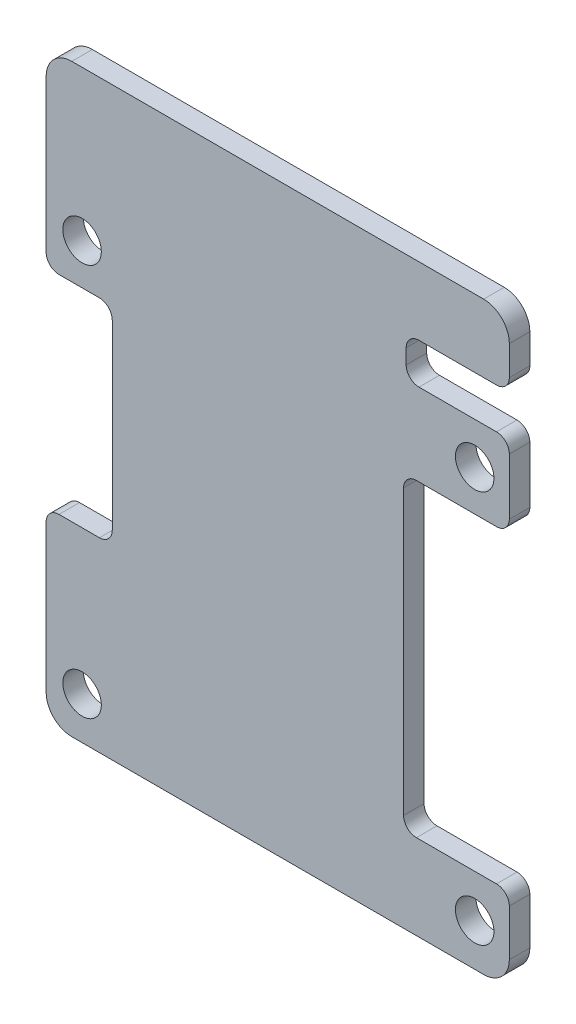
SolidWorks part; units mm, degrees
ref_plane "Front Plane" through (0, 0, 0) normal (0, 0, 1) x (1, 0, 0)
ref_plane "Top Plane" through (0, 0, 0) normal (0, 1, 0) x (1, 0, 0)
ref_plane "Right Plane" through (0, 0, 0) normal (1, 0, 0) x (0, 0, -1)
sketch "Board1"
  dimension "D3" = 2
  dimension "D1" = 54
  dimension "D2" = 36.1
  dimension "D6" = 30.6
  dimension "D7" = 30.6
  dimension "D8" = 30.6
  dimension "D10" = 2.7
  dimension "D9" = 3
  dimension "D4" = 11.7
  dimension "D5" = 30.6
sketch "Board2" plane through (0, 0, 0) normal (0, 0, 1) x (1, 0, 0)
  line L0 (115.6499, 52) -> (115.6499, 2)
  line L1 (117.6499, 0) -> (149.7499, 0)
  line L2 (151.7499, 2) -> (151.7499, 52)
  line L3 (149.7499, 54) -> (117.6499, 54)
  arc A0 (149.7499, 0) -> (151.7499, 2) centre (149.7499, 2) ccw
  arc A1 (115.6499, 2) -> (117.6499, 0) centre (117.6499, 2) ccw
  arc A2 (115.6499, 52) -> (117.6499, 54) centre (117.6499, 52) cw
  arc A3 (151.7499, 52) -> (149.7499, 54) centre (149.7499, 52) ccw
  circle A4 centre (149.0499, 42.3) radius 1.5
  circle A5 centre (149.0499, 11.7) radius 1.5
  circle A6 centre (118.4499, 11.7) radius 1.5
  circle A7 centre (118.4499, 42.3) radius 1.5
  point P7 (151.7499, 0)
  point P12 (115.6499, 54)
  point P15 (151.7499, 54)
  dimension "D3" = 2
  dimension "D6" = 30.6
  dimension "D7" = 30.6
  dimension "D5" = 30.6
  dimension "D4" = 3
  dimension "D1" = 36.1
  dimension "D2" = 54
  dimension "D8" = 2.7
  dimension "D9" = 11.7
sketch "Board3" plane through (0, 0, 0) normal (0, 0, 1) x (1, 0, 0)
  line L0 (12.8709, 54) -> (44.9709, 54)
  line L1 (46.9709, 52) -> (46.9709, 49.7006)
  line L2 (45.9709, 48.7006) -> (39.9314, 48.7006)
  line L3 (38.9314, 47.7006) -> (38.9314, 46.5412)
  line L4 (39.9314, 45.5412) -> (45.9709, 45.5412)
  line L5 (46.9709, 44.5412) -> (46.9709, 40.1406)
  line L6 (45.9709, 39.1406) -> (39.7286, 39.1406)
  line L7 (38.7286, 38.1406) -> (38.7286, 16.0292)
  line L8 (39.7286, 15.0292) -> (45.9709, 15.0292)
  line L9 (46.9709, 14.0292) -> (46.9709, 10.4124)
  line L10 (44.9709, 8.4124) -> (12.8709, 8.4124)
  line L11 (10.8709, 10.4124) -> (10.8709, 21.9198)
  line L12 (11.8709, 22.9198) -> (15.0232, 22.9198)
  line L13 (16.0232, 23.9198) -> (16.0232, 38.1107)
  line L14 (15.0232, 39.1107) -> (11.8709, 39.1107)
  line L15 (10.8709, 40.1107) -> (10.8709, 52)
  arc A0 (44.9709, 54) -> (46.9709, 52) centre (44.9709, 52) cw
  arc A1 (46.9709, 10.4124) -> (44.9709, 8.4124) centre (44.9709, 10.4124) cw
  arc A2 (12.8709, 8.4124) -> (10.8709, 10.4124) centre (12.8709, 10.4124) cw
  arc A3 (12.8709, 54) -> (10.8709, 52) centre (12.8709, 52) ccw
  arc A4 (46.9709, 49.7006) -> (45.9709, 48.7006) centre (45.9709, 49.7006) cw
  arc A5 (39.9314, 48.7006) -> (38.9314, 47.7006) centre (39.9314, 47.7006) ccw
  arc A6 (38.9314, 46.5412) -> (39.9314, 45.5412) centre (39.9314, 46.5412) ccw
  arc A7 (45.9709, 45.5412) -> (46.9709, 44.5412) centre (45.9709, 44.5412) cw
  arc A8 (46.9709, 40.1406) -> (45.9709, 39.1406) centre (45.9709, 40.1406) cw
  arc A9 (39.7286, 39.1406) -> (38.7286, 38.1406) centre (39.7286, 38.1406) ccw
  arc A10 (38.7286, 16.0292) -> (39.7286, 15.0292) centre (39.7286, 16.0292) ccw
  arc A11 (45.9709, 15.0292) -> (46.9709, 14.0292) centre (45.9709, 14.0292) cw
  arc A12 (10.8709, 21.9198) -> (11.8709, 22.9198) centre (11.8709, 21.9198) cw
  arc A13 (15.0232, 22.9198) -> (16.0232, 23.9198) centre (15.0232, 23.9198) ccw
  arc A14 (16.0232, 38.1107) -> (15.0232, 39.1107) centre (15.0232, 38.1107) ccw
  arc A15 (11.8709, 39.1107) -> (10.8709, 40.1107) centre (11.8709, 40.1107) cw
  circle A16 centre (13.6709, 42.3) radius 1.5
  circle A17 centre (44.2709, 42.3) radius 1.5
  circle A18 centre (13.6709, 11.7) radius 1.5
  circle A19 centre (44.2709, 11.7) radius 1.5
  dimension "D3" = 2
  dimension "D4" = 1
  dimension "D5" = 3
  dimension "D1" = 54
  dimension "D2" = 36.1
  dimension "D6" = 30.6
  dimension "D7" = 30.6
  dimension "D9" = 30.6
  dimension "D8" = 30.6
  dimension "D10" = 2.7
  dimension "D11" = 11.7
extrude "Бобышка-Вытянуть4" add sketch "Board3" along normal blind 1.6
equation "\"D7@Board3\" = \"D6@Board3\""
equation "\"D9@Board3\" = \"D6@Board3\""
equation "\"D8@Board3\" = \"D6@Board3\""
equation "\"D8@Board1\"=\"D6@Board1\""
equation "\"D5@Board1\"=\"D6@Board1\""
equation "\"D7@Board1\"=\"D6@Board1\""
equation "\"D6@Board2\"=\"D5@Board2\""
equation "\"D7@Board2\"=\"D5@Board2\""
